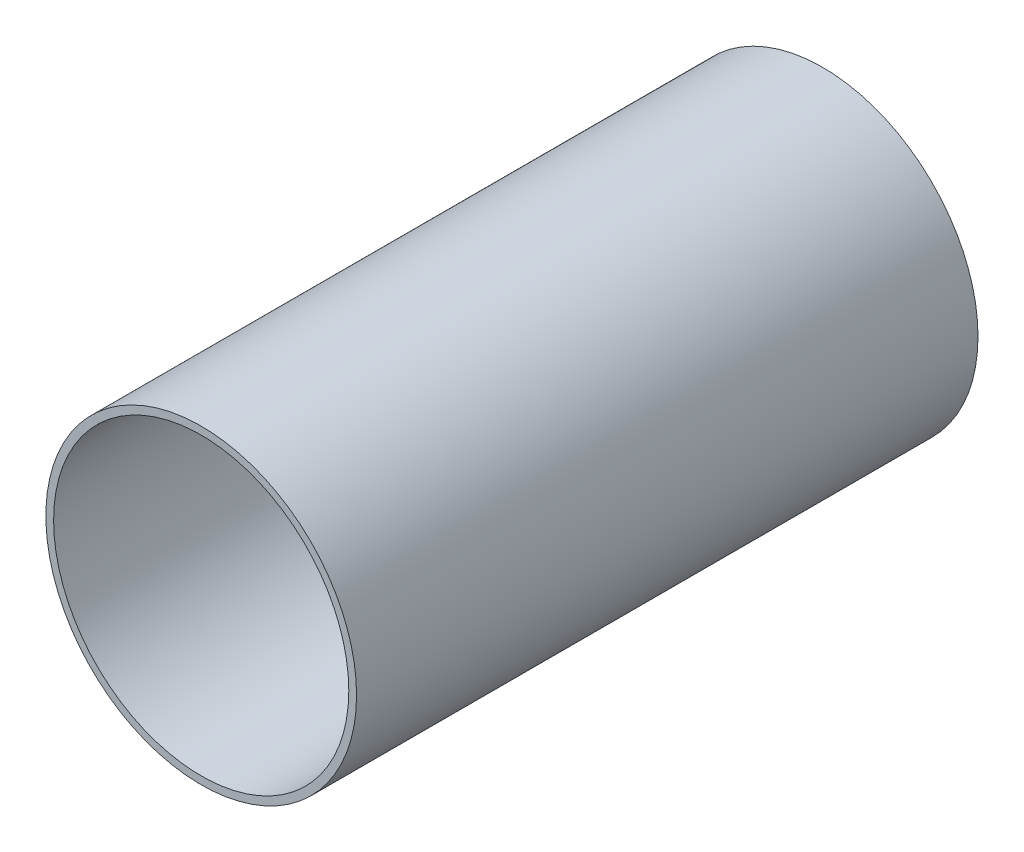
SolidWorks part; units mm, degrees
material "6061 合金"
ref_plane "前视基准面" through (0, 0, 0) normal (0, 0, 1) x (1, 0, 0)
ref_plane "上视基准面" through (0, 0, 0) normal (0, 1, 0) x (1, 0, 0)
ref_plane "右视基准面" through (0, 0, 0) normal (1, 0, 0) x (0, 0, -1)
sketch "草图1" plane through (0, 0, 0) normal (0, 0, 1) x (1, 0, 0)
  circle A0 centre (0, 0) radius 9.5
  circle A1 centre (0, 0) radius 10
  dimension "D1" = 19
  dimension "D2" = 20
extrude "凸台-拉伸1" add sketch "草图1" along normal blind 40
